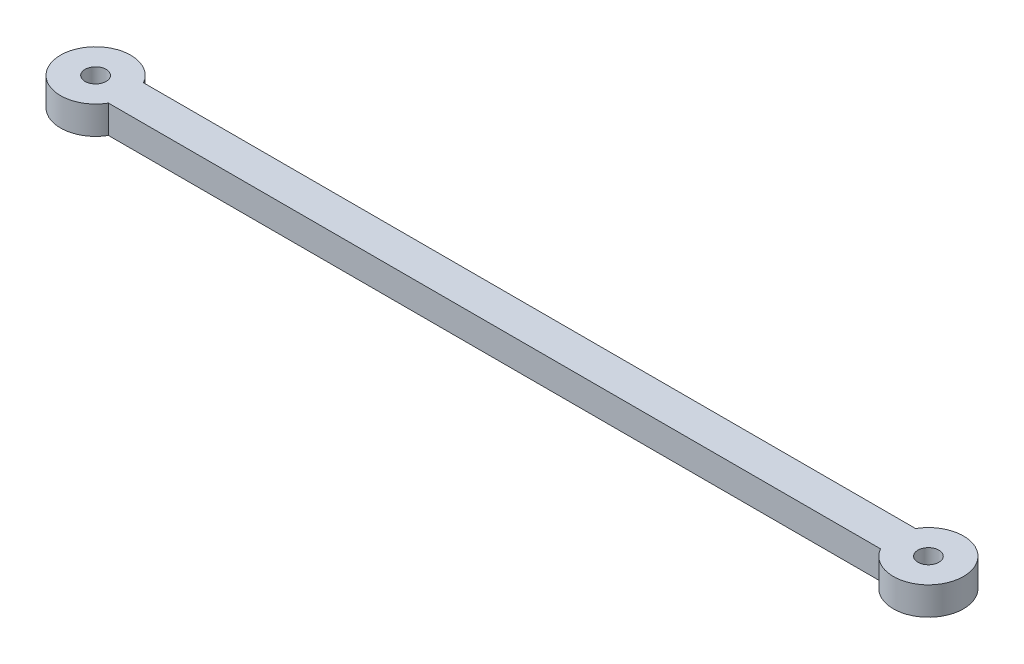
SolidWorks part; units mm, degrees
ref_plane "Front Plane" through (0, 0, 0) normal (0, 0, 1) x (1, 0, 0)
ref_plane "Top Plane" through (0, 0, 0) normal (0, 1, 0) x (1, 0, 0)
ref_plane "Right Plane" through (0, 0, 0) normal (1, 0, 0) x (0, 0, -1)
sketch "Sketch1" plane through (0, 0, 0) normal (0, 1, 0) x (1, 0, 0)
  line L0 (-55, 2.5) -> (55, 2.5)
  line L1 (-55, -2.5) -> (55, -2.5)
  line L2 (-55, 0) -> (55, 0) construction
  arc A1 (-55, 2.5) -> (-55, -2.5) centre (-59.3301, 0) ccw
  arc A2 (55, 2.5) -> (55, -2.5) centre (59.3301, 0) cw
  dimension "D2" = 55
  dimension "D3" = 5
  dimension "D7" = 5
  dimension "D1" = 5
  dimension "D4" = 110
  dimension "D5" = 110
  dimension "D6" = 2.5
extrude "Boss-Extrude1" add sketch "Sketch1" along normal blind 4
sketch "Sketch2" plane through (0, 4, 0) normal (0, 1, 0) x (1, 0, 0)
  circle A0 centre (-59.3301, 0) radius 1.5
  circle A1 centre (59.3301, 0) radius 1.5
  dimension "D1" = 3
  dimension "D2" = 3
extrude "Cut-Extrude1" cut sketch "Sketch2" against normal through all
